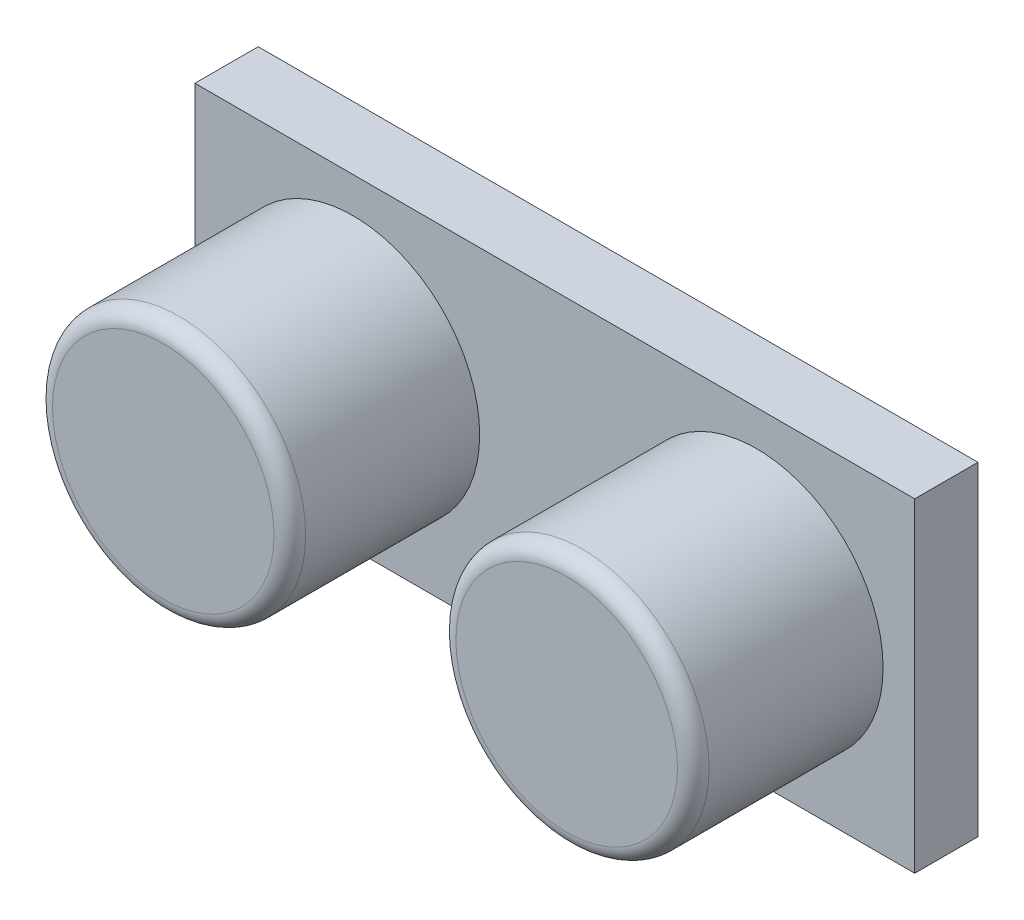
SolidWorks part; units mm, degrees
ref_plane "Front Plane" through (0, 0, 0) normal (0, 0, 1) x (1, 0, 0)
ref_plane "Top Plane" through (0, 0, 0) normal (0, 1, 0) x (1, 0, 0)
ref_plane "Right Plane" through (0, 0, 0) normal (1, 0, 0) x (0, 0, -1)
sketch "Sketch1" plane through (0, 0, 0) normal (0, 0, 1) x (1, 0, 0)
  line L1 (-22.75, -10.25) -> (22.75, -10.25)
  line L2 (-22.75, -10.25) -> (-22.75, 10.25)
  line L3 (-22.75, 10.25) -> (22.75, 10.25)
  line L4 (22.75, -10.25) -> (22.75, 10.25)
  line L5 (-22.75, -10.25) -> (22.75, 10.25) construction
  line L6 (-22.75, 10.25) -> (22.75, -10.25) construction
  point P0 (0, 0)
extrude "Boss-Extrude1" add sketch "Sketch1" along normal blind 4
sketch "Sketch2" plane through (0, 0, 4) normal (0, 0, 1) x (1, 0, 0)
  line L0 (-22.75, 10.25) -> (-22.75, -10.25) construction
  line L1 (22.75, -10.25) -> (22.75, 10.25) construction
  circle A0 centre (-12.75, 0) radius 8
  circle A1 centre (12.75, 0) radius 8
  dimension "D1" = 10
  dimension "D2" = 10
extrude "Boss-Extrude2" add sketch "Sketch2" along normal blind 12
fillet "Fillet1" radius 1 2 edges at (20.75, 0, 16) (-4.75, 0, 16)
